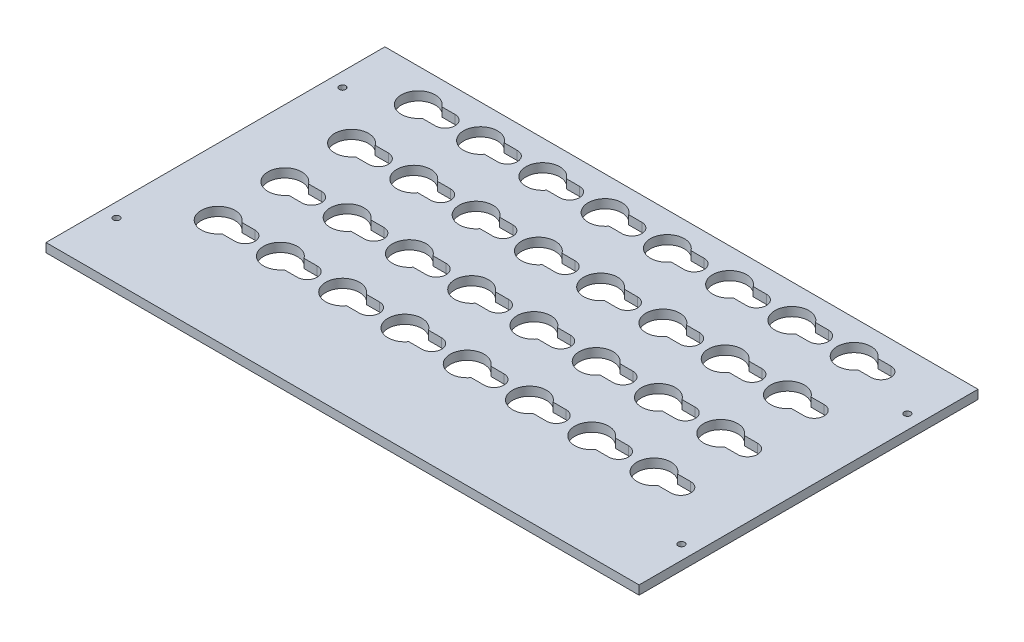
SolidWorks part; units mm, degrees
ref_plane "Front Plane" through (0, 0, 0) normal (0, 0, 1) x (1, 0, 0)
ref_plane "Top Plane" through (0, 0, 0) normal (0, 1, 0) x (1, 0, 0)
ref_plane "Right Plane" through (0, 0, 0) normal (1, 0, 0) x (0, 0, -1)
sketch "Sketch1" plane through (0, 0, 0) normal (0, 1, 0) x (1, 0, 0)
  line L0 (36.1892, -10.555) -> (42.065, -10.555)
  line L1 (0, 0) -> (266.7, 0)
  line L2 (0, 0) -> (0, -152.4)
  line L3 (0, -152.4) -> (266.7, -152.4)
  line L4 (266.7, 0) -> (266.7, -152.4)
  line L5 (36.1892, -19.445) -> (42.065, -19.445)
  line L6 (64.1892, -10.555) -> (70.065, -10.555)
  line L7 (64.1892, -19.445) -> (70.065, -19.445)
  line L8 (92.1892, -10.555) -> (98.065, -10.555)
  line L9 (92.1892, -19.445) -> (98.065, -19.445)
  line L10 (120.1892, -10.555) -> (126.065, -10.555)
  line L11 (120.1892, -19.445) -> (126.065, -19.445)
  line L12 (64.1892, -40.555) -> (70.065, -40.555)
  line L13 (64.1892, -49.445) -> (70.065, -49.445)
  line L14 (92.1892, -40.555) -> (98.065, -40.555)
  line L15 (92.1892, -49.445) -> (98.065, -49.445)
  line L16 (120.1892, -40.555) -> (126.065, -40.555)
  line L17 (120.1892, -49.445) -> (126.065, -49.445)
  line L18 (64.1892, -70.555) -> (70.065, -70.555)
  line L19 (64.1892, -79.445) -> (70.065, -79.445)
  line L20 (92.1892, -70.555) -> (98.065, -70.555)
  line L21 (92.1892, -79.445) -> (98.065, -79.445)
  line L22 (120.1892, -70.555) -> (126.065, -70.555)
  line L23 (120.1892, -79.445) -> (126.065, -79.445)
  line L24 (64.1892, -100.555) -> (70.065, -100.555)
  line L25 (64.1892, -109.445) -> (70.065, -109.445)
  line L26 (92.1892, -100.555) -> (98.065, -100.555)
  line L27 (92.1892, -109.445) -> (98.065, -109.445)
  line L28 (120.1892, -100.555) -> (126.065, -100.555)
  line L29 (120.1892, -109.445) -> (126.065, -109.445)
  line L30 (36.1892, -40.555) -> (42.065, -40.555)
  line L31 (36.1892, -49.445) -> (42.065, -49.445)
  line L32 (36.1892, -70.555) -> (42.065, -70.555)
  line L33 (36.1892, -79.445) -> (42.065, -79.445)
  line L34 (36.1892, -100.555) -> (42.065, -100.555)
  line L35 (36.1892, -109.445) -> (42.065, -109.445)
  line L36 (148.1892, -10.555) -> (154.065, -10.555)
  line L37 (148.1892, -19.445) -> (154.065, -19.445)
  line L38 (176.1892, -10.555) -> (182.065, -10.555)
  line L39 (176.1892, -19.445) -> (182.065, -19.445)
  line L40 (204.1892, -10.555) -> (210.065, -10.555)
  line L41 (204.1892, -19.445) -> (210.065, -19.445)
  line L42 (232.1892, -10.555) -> (238.065, -10.555)
  line L43 (232.1892, -19.445) -> (238.065, -19.445)
  line L44 (148.1892, -40.555) -> (154.065, -40.555)
  line L45 (148.1892, -49.445) -> (154.065, -49.445)
  line L46 (176.1892, -40.555) -> (182.065, -40.555)
  line L47 (176.1892, -49.445) -> (182.065, -49.445)
  line L48 (204.1892, -40.555) -> (210.065, -40.555)
  line L49 (204.1892, -49.445) -> (210.065, -49.445)
  line L50 (232.1892, -40.555) -> (238.065, -40.555)
  line L51 (232.1892, -49.445) -> (238.065, -49.445)
  line L52 (148.1892, -70.555) -> (154.065, -70.555)
  line L53 (148.1892, -79.445) -> (154.065, -79.445)
  line L54 (176.1892, -70.555) -> (182.065, -70.555)
  line L55 (176.1892, -79.445) -> (182.065, -79.445)
  line L56 (204.1892, -70.555) -> (210.065, -70.555)
  line L57 (204.1892, -79.445) -> (210.065, -79.445)
  line L58 (232.1892, -70.555) -> (238.065, -70.555)
  line L59 (232.1892, -79.445) -> (238.065, -79.445)
  line L60 (148.1892, -100.555) -> (154.065, -100.555)
  line L61 (148.1892, -109.445) -> (154.065, -109.445)
  line L62 (176.1892, -100.555) -> (182.065, -100.555)
  line L63 (176.1892, -109.445) -> (182.065, -109.445)
  line L64 (204.1892, -100.555) -> (210.065, -100.555)
  line L65 (204.1892, -109.445) -> (210.065, -109.445)
  line L66 (232.1892, -100.555) -> (238.065, -100.555)
  line L67 (232.1892, -109.445) -> (238.065, -109.445)
  circle A0 centre (30, -15) radius 7.62
  circle A1 centre (42.065, -15) radius 4.445
  circle A2 centre (58, -15) radius 7.62
  circle A3 centre (70.065, -15) radius 4.445
  circle A4 centre (86, -15) radius 7.62
  circle A5 centre (98.065, -15) radius 4.445
  circle A6 centre (114, -15) radius 7.62
  circle A7 centre (126.065, -15) radius 4.445
  circle A8 centre (58, -45) radius 7.62
  circle A9 centre (70.065, -45) radius 4.445
  circle A10 centre (86, -45) radius 7.62
  circle A11 centre (98.065, -45) radius 4.445
  circle A12 centre (114, -45) radius 7.62
  circle A13 centre (126.065, -45) radius 4.445
  circle A14 centre (58, -75) radius 7.62
  circle A15 centre (70.065, -75) radius 4.445
  circle A16 centre (86, -75) radius 7.62
  circle A17 centre (98.065, -75) radius 4.445
  circle A18 centre (114, -75) radius 7.62
  circle A19 centre (126.065, -75) radius 4.445
  circle A20 centre (58, -105) radius 7.62
  circle A21 centre (70.065, -105) radius 4.445
  circle A22 centre (86, -105) radius 7.62
  circle A23 centre (98.065, -105) radius 4.445
  circle A24 centre (114, -105) radius 7.62
  circle A25 centre (126.065, -105) radius 4.445
  circle A26 centre (30, -45) radius 7.62
  circle A27 centre (42.065, -45) radius 4.445
  circle A28 centre (30, -75) radius 7.62
  circle A29 centre (42.065, -75) radius 4.445
  circle A30 centre (30, -105) radius 7.62
  circle A31 centre (42.065, -105) radius 4.445
  circle A32 centre (142, -15) radius 7.62
  circle A33 centre (154.065, -15) radius 4.445
  circle A34 centre (170, -15) radius 7.62
  circle A35 centre (182.065, -15) radius 4.445
  circle A36 centre (198, -15) radius 7.62
  circle A37 centre (210.065, -15) radius 4.445
  circle A38 centre (226, -15) radius 7.62
  circle A39 centre (238.065, -15) radius 4.445
  circle A40 centre (142, -45) radius 7.62
  circle A41 centre (154.065, -45) radius 4.445
  circle A42 centre (170, -45) radius 7.62
  circle A43 centre (182.065, -45) radius 4.445
  circle A44 centre (198, -45) radius 7.62
  circle A45 centre (210.065, -45) radius 4.445
  circle A46 centre (226, -45) radius 7.62
  circle A47 centre (238.065, -45) radius 4.445
  circle A48 centre (142, -75) radius 7.62
  circle A49 centre (154.065, -75) radius 4.445
  circle A50 centre (170, -75) radius 7.62
  circle A51 centre (182.065, -75) radius 4.445
  circle A52 centre (198, -75) radius 7.62
  circle A53 centre (210.065, -75) radius 4.445
  circle A54 centre (226, -75) radius 7.62
  circle A55 centre (238.065, -75) radius 4.445
  circle A56 centre (142, -105) radius 7.62
  circle A57 centre (154.065, -105) radius 4.445
  circle A58 centre (170, -105) radius 7.62
  circle A59 centre (182.065, -105) radius 4.445
  circle A60 centre (198, -105) radius 7.62
  circle A61 centre (210.065, -105) radius 4.445
  circle A62 centre (226, -105) radius 7.62
  circle A63 centre (238.065, -105) radius 4.445
  circle A80 centre (6.35, -25.4) radius 1.4732
  circle A81 centre (6.35, -127) radius 1.4732
  circle A82 centre (260.35, -25.4) radius 1.4732
  circle A83 centre (260.35, -127) radius 1.4732
  dimension "D1" = 8.89
  dimension "D3" = 15.24
  dimension "D11" = 2.9464
  dimension "D4" = 15
  dimension "D5" = 30
  dimension "D8" = 28
  dimension "D9" = 30
  dimension "D10" = 152.4
  dimension "D12" = 6.35
  dimension "D13" = 6.35
  dimension "D14" = 25.4
  dimension "D15" = 25.4
  dimension "D2" = 254
  dimension "D6" = 8
  dimension "D7" = 4
extrude "Boss-Extrude1" add sketch "Sketch1" along normal blind 4 contours L4 L1 L2 L3 A31 L35 A30 L34 A29 L33 A28 L32 A27 L31 A26 L30 A25 L29 A24 L28 A23 L27 A22 L26 A21 L25 A20 L24 A19 L23 A18 L22 A17 L21 A16 L20 A15 L19 A14 L18 A13
equation "\"D7@Sketch2\"=\"D5@Sketch2\""
equation "\"D6@3DSketch1\"=\"D5@3DSketch1\""
equation "\"D5@3DSketch1\"=\"D1@3DSketch1\""
equation "\"D1@3DSketch1\"=\"D2@3DSketch1\""
equation "\"D7@3DSketch1\"=\"D8@3DSketch1\""
equation "\"D3@3DSketch1\"=\"D4@3DSketch1\""
equation "\"D13@Sketch1\"=\"D12@Sketch1\""
